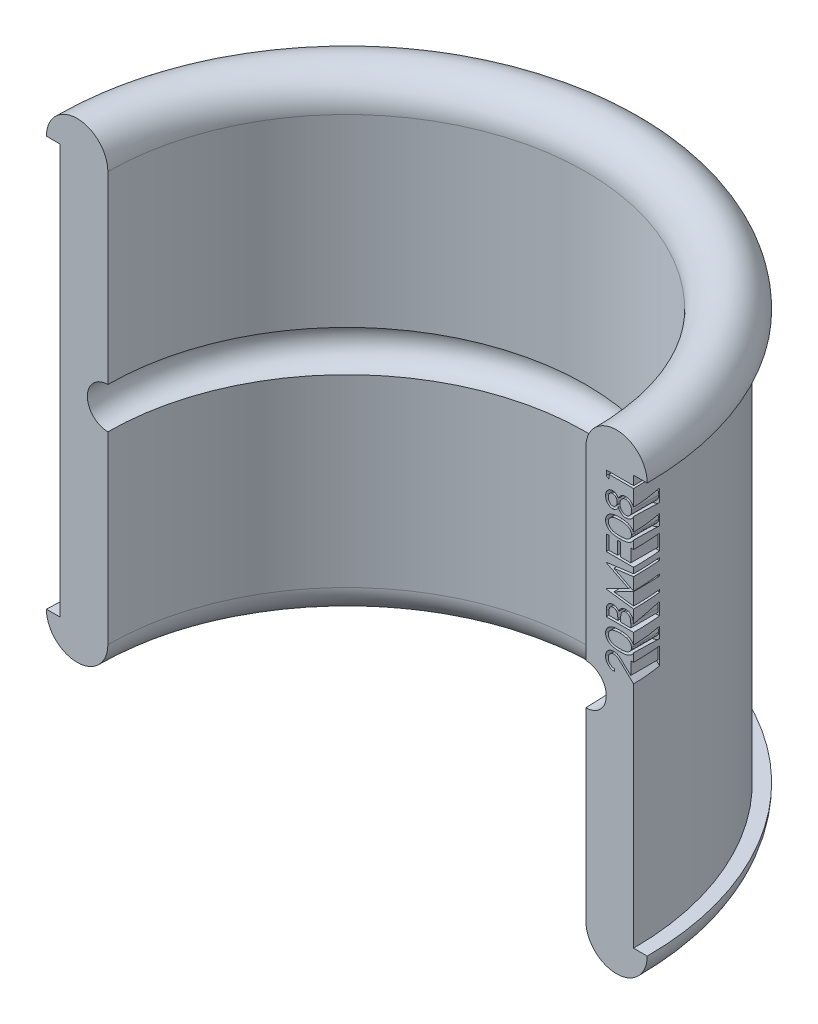
SolidWorks part; units mm, degrees
ref_plane "Front Plane" through (0, 0, 0) normal (0, 0, 1) x (1, 0, 0)
ref_plane "Top Plane" through (0, 0, 0) normal (0, 1, 0) x (1, 0, 0)
ref_plane "Right Plane" through (0, 0, 0) normal (1, 0, 0) x (0, 0, -1)
sketch "Sketch2" plane through (0, 0, 0) normal (0, 0, 1) x (1, 0, 0)
  line L0 (2.25, 1.5) -> (2.25, 15)
  line L1 (-2.25, -15) -> (2.25, -15) construction
  line L3 (-2.25, 15) -> (2.25, 15) construction
  line L4 (2.25, -15) -> (2.25, -1.5)
  line L5 (-2.25, -15) -> (2.25, 15) construction
  line L6 (-2.25, 15) -> (2.25, -15) construction
  line L7 (-2.25, 15) -> (-1.25, 15)
  line L9 (-2.25, -15) -> (-1.25, -15)
  line L10 (-1.25, 15) -> (-1.25, -15)
  line L11 (19.75, 15) -> (19.75, -15) construction
  arc A0 (-2.25, 15) -> (2.25, 15) centre (0, 15) cw
  arc A1 (-2.25, -15) -> (2.25, -15) centre (0, -15) ccw
  arc A2 (2.25, 1.5) -> (2.25, -1.5) centre (2.25, 0) ccw
  point P0 (0, 0)
  dimension "D4" = 1.5
  dimension "D1" = 30
  dimension "D2" = 4.5
  dimension "D3" = 1
  dimension "D5" = 17.5
revolve "Revolve2" add sketch "Sketch2" angle 180 about L11
sketch "Sketch3" plane through (0, 0, 0) normal (0, 0, 1) x (1, 0, 0)
  text T0 "20BME081" font "Century Gothic" height 2
extrude "Cut-Extrude1" cut sketch "Sketch3" against normal blind 2
